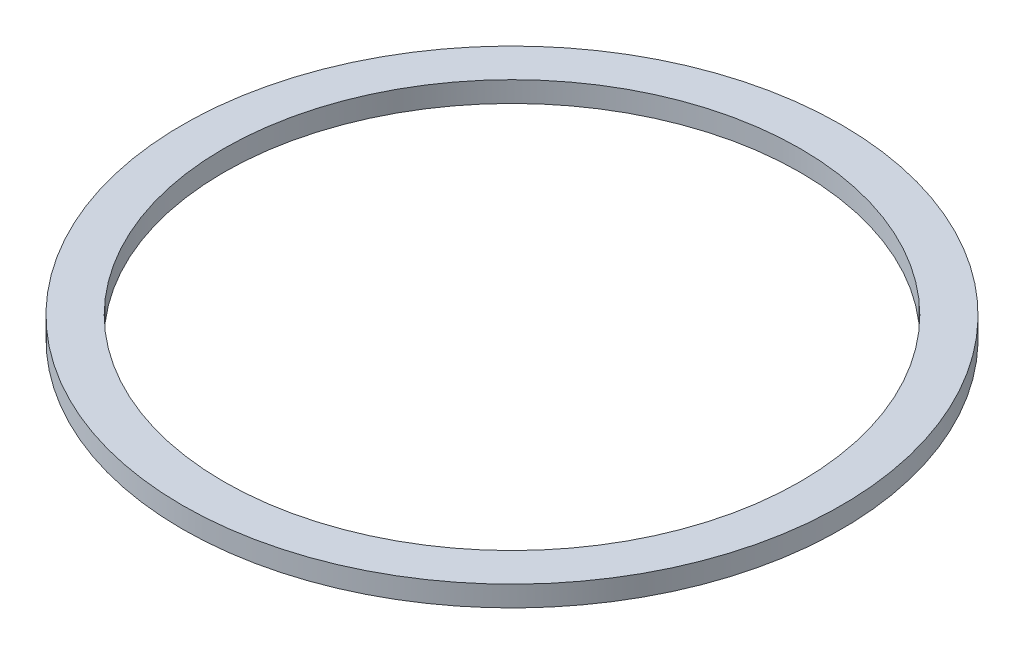
SolidWorks part; units mm, degrees
material "ABS"
ref_plane "Front Plane" through (0, 0, 0) normal (0, 0, 1) x (1, 0, 0)
ref_plane "Top Plane" through (0, 0, 0) normal (0, 1, 0) x (1, 0, 0)
ref_plane "Right Plane" through (0, 0, 0) normal (1, 0, 0) x (0, 0, -1)
sketch "Sketch1" plane through (0, 0, 0) normal (0, 1, 0) x (1, 0, 0)
  circle A0 centre (0, 0) radius 8
  circle A1 centre (0, 0) radius 7
  dimension "D1" = 16
  dimension "D2" = 14
extrude "Boss-Extrude1" add sketch "Sketch1" along normal blind 0.5
